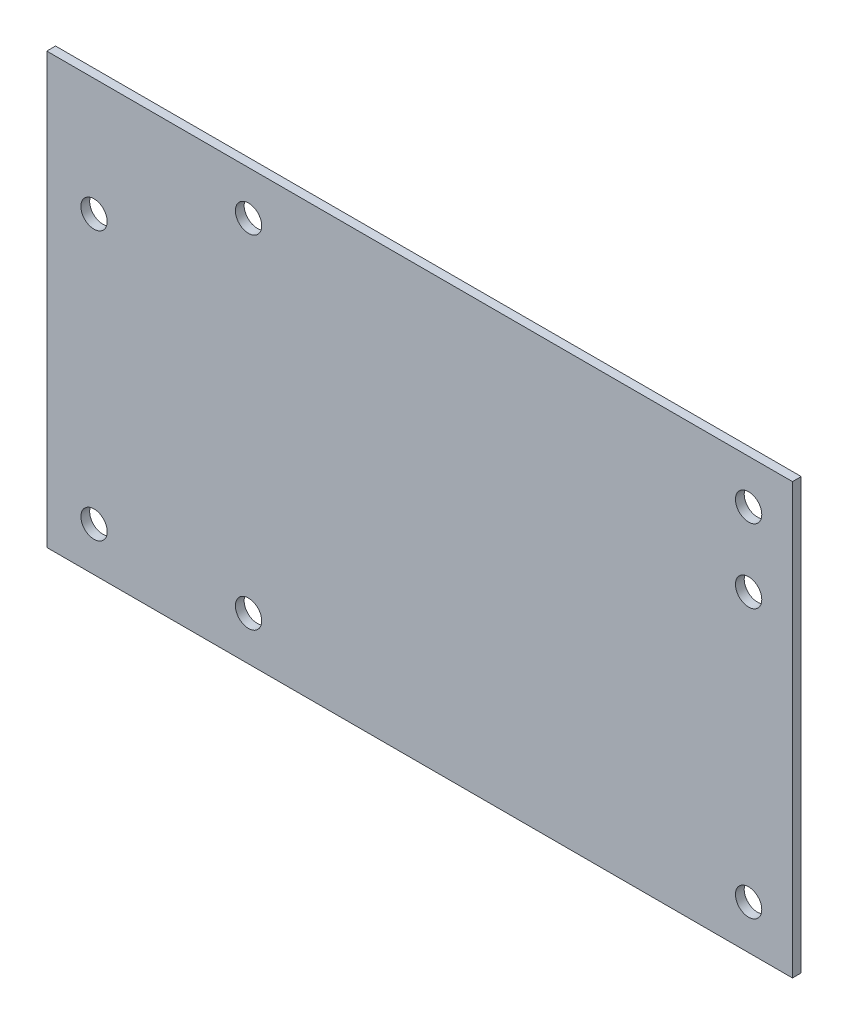
SolidWorks part; units mm, degrees
ref_plane "Спереди" through (0, 0, 0) normal (0, 0, 1) x (1, 0, 0)
ref_plane "Сверху" through (0, 0, 0) normal (0, 1, 0) x (1, 0, 0)
ref_plane "Справа" through (0, 0, 0) normal (1, 0, 0) x (0, 0, -1)
sketch "Эскиз1" plane through (0, 0, 0) normal (0, 0, 1) x (1, 0, 0)
  line L1 (0, 0) -> (-85, 0)
  line L2 (0, 0) -> (0, 49)
  line L3 (0, 49) -> (-85, 49)
  line L4 (-85, 0) -> (-85, 49)
  line L5 (-5, 5) -> (-79.61, 5) construction
  line L6 (-5, 5) -> (-5, 35.61) construction
  line L7 (-5, 35.61) -> (-79.61, 35.61) construction
  line L8 (-79.61, 5) -> (-79.61, 35.61) construction
  line L9 (-5, 5) -> (-79.61, 35.61) construction
  line L10 (-5, 35.61) -> (-79.61, 5) construction
  circle A0 centre (-5, 5) radius 1.5
  circle A1 centre (-5, 35.61) radius 1.5
  circle A2 centre (-79.61, 35.61) radius 1.5
  circle A3 centre (-79.61, 5) radius 1.5
  circle A4 centre (-5, 44) radius 1.5
  circle A5 centre (-62, 44) radius 1.5
  circle A6 centre (-62, 5) radius 1.5
  point P13 (-42.305, 20.305)
  point P18 (0, 0)
  point P19 (0, 0)
  point P20 (0, 0)
  point P21 (0, 0)
  point P22 (-1.8297, 42.4286)
  point P25 (-58.5461, 42.6949)
  point P26 (-4.9044, 4.4727)
  point P27 (0, 0)
  point P28 (-62, 44)
  point P29 (-73.5265, 27.3873)
  dimension "D1" = 3
  dimension "D2" = 85
  dimension "D3" = 39
  dimension "D4" = 5
  dimension "D5" = 5
  dimension "D6" = 57
  dimension "D7" = 5
  dimension "D8" = 74.61
  dimension "D9" = 30.61
extrude "Бобышка-Вытянуть1" add sketch "Эскиз1" along normal blind 1
